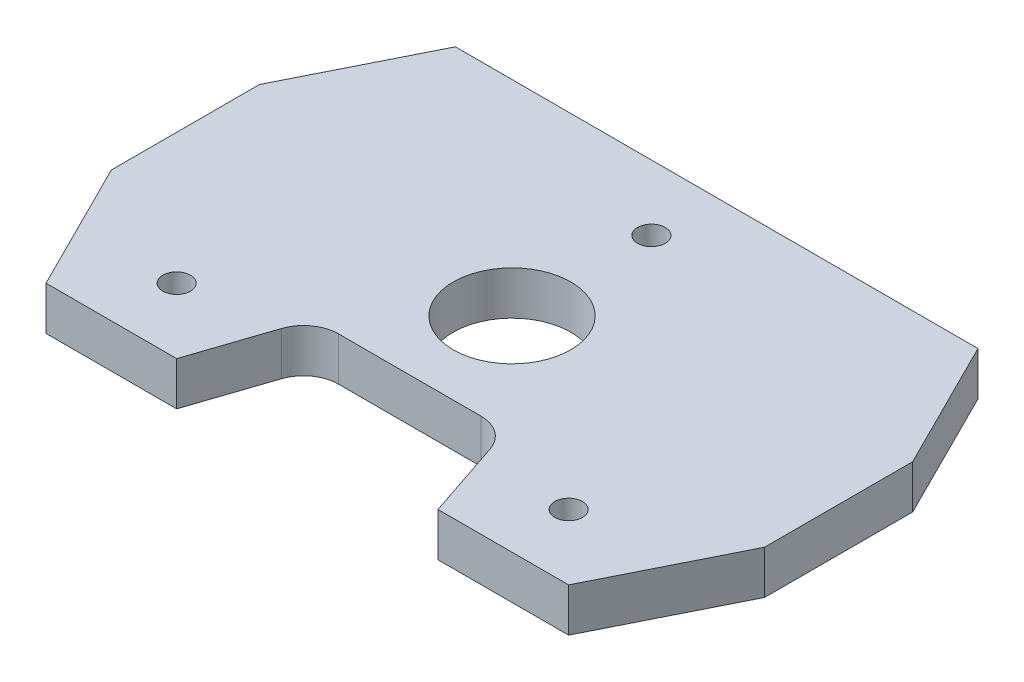
SolidWorks part; units mm, degrees
ref_plane "Front" through (0, 0, 0) normal (0, 0, 1) x (1, 0, 0)
ref_plane "Top" through (0, 0, 0) normal (0, 1, 0) x (1, 0, 0)
ref_plane "Right" through (0, 0, 0) normal (1, 0, 0) x (0, 0, -1)
sketch "Sketch1" plane through (0, 0, 0) normal (0, 1, 0) x (1, 0, 0)
  line L0 (-60, 27.301) -> (60, 27.301)
  line L1 (-60, 27.301) -> (-75, -2.699)
  line L2 (-75, -2.699) -> (-75, -36.699)
  line L3 (-75, -36.699) -> (-60, -66.699)
  line L7 (60, 27.301) -> (75, -2.699)
  line L8 (75, -2.699) -> (75, -36.699)
  line L9 (75, -36.699) -> (60, -66.699)
  line L14 (-60, -66.699) -> (-30, -66.699)
  line L15 (30, -66.699) -> (60, -66.699)
  line L16 (-30, -66.699) -> (-23.9492, -48.6555)
  line L17 (30, -66.699) -> (23.9492, -48.6555)
  line L21 (16.3643, -43.199) -> (-16.3643, -43.199)
  circle A1 centre (-45, -51.699) radius 3.175
  circle A2 centre (0, 12.301) radius 3.175
  circle A3 centre (45, -51.699) radius 3.175
  circle A4 centre (0, -19.699) radius 13.5
  arc A5 (-16.3643, -43.199) -> (-23.9492, -48.6555) centre (-16.3643, -51.199) ccw
  arc A6 (23.9492, -48.6555) -> (16.3643, -43.199) centre (16.3643, -51.199) ccw
  dimension "D19" = 6.35
  dimension "D20" = 6.35
  dimension "D21" = 6.35
  dimension "D8" = 27
  dimension "D17" = 23.5
  dimension "D1" = 120
  dimension "D2" = 34
  dimension "D3" = 15
  dimension "D4" = 15
  dimension "D5" = 15
  dimension "D6" = 47
  dimension "D7" = 15
  dimension "D9" = 34
  dimension "D10" = 30
  dimension "D11" = 30
  dimension "D12" = 30
  dimension "D13" = 30
  dimension "D14" = 15
  dimension "D15" = 30
  dimension "D16" = 30
  dimension "D18" = 15
extrude "Boss-Extrude1" add sketch "Sketch1" along normal blind 10
